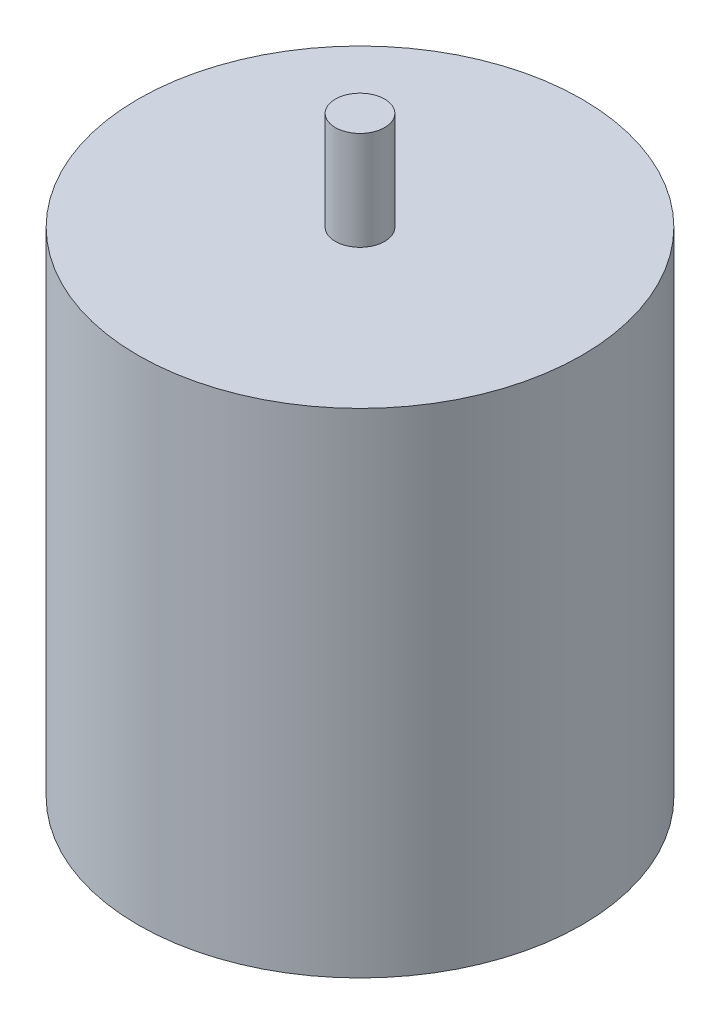
SolidWorks part; units mm, degrees
ref_plane "Plan de face" through (0, 0, 0) normal (0, 0, 1) x (1, 0, 0)
ref_plane "Plan de dessus" through (0, 0, 0) normal (0, 1, 0) x (1, 0, 0)
ref_plane "Plan de droite" through (0, 0, 0) normal (1, 0, 0) x (0, 0, -1)
sketch "Esquisse1" plane through (0, 0, 0) normal (0, 1, 0) x (1, 0, 0)
  circle A0 centre (0, 0) radius 44.9951
extrude "Boss.-Extru.1" add sketch "Esquisse1" along normal blind 100
sketch "Esquisse2" plane through (0, 100, 0) normal (0, 1, 0) x (1, 0, 0)
  circle A0 centre (0, 0) radius 5
  dimension "D1" = 10
extrude "Boss.-Extru.2" add sketch "Esquisse2" along normal blind 20
